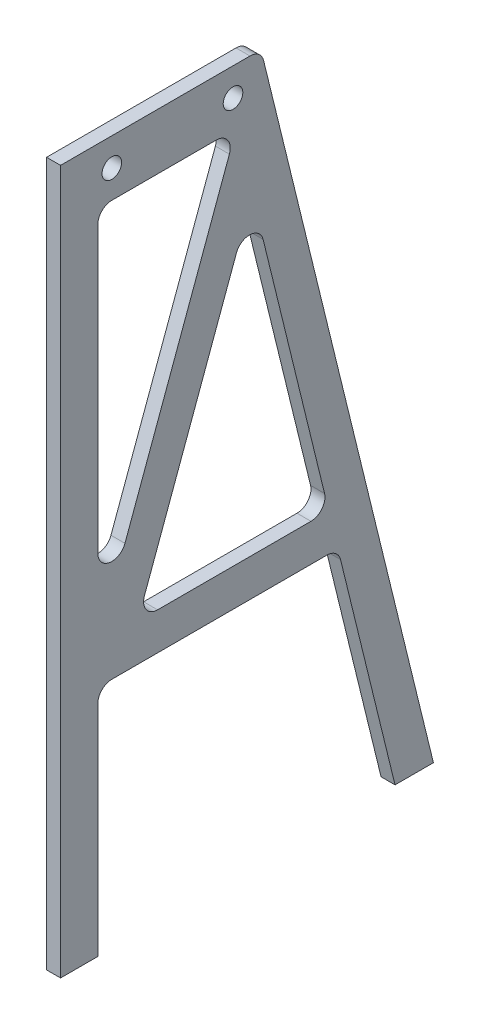
SolidWorks part; units mm, degrees
material "Thornel Mat VMA"
ref_plane "Front Plane" through (0, 0, 0) normal (0, 0, 1) x (1, 0, 0)
ref_plane "Top Plane" through (0, 0, 0) normal (0, 1, 0) x (1, 0, 0)
ref_plane "Right Plane" through (0, 0, 0) normal (1, 0, 0) x (0, 0, -1)
sketch "Sketch1" plane through (0, 0, 0) normal (1, 0, 0) x (0, 0, -1)
  line L0 (0, 0) -> (0, 75.5)
  line L2 (21.5, 75.5) -> (40, 0)
  line L3 (40, 0) -> (35.8817, 0)
  line L4 (35.8817, 0) -> (29.7558, 25)
  line L5 (29.7558, 25) -> (4, 25)
  line L6 (4, 25) -> (4, 0)
  line L7 (4, 0) -> (0, 0)
  line L8 (4, 69.5) -> (18.8519, 69.5)
  line L9 (18.8519, 69.5) -> (4, 29)
  line L10 (4, 29) -> (4, 69.5)
  line L11 (8.2605, 29) -> (20.5584, 62.5355)
  line L12 (20.5584, 62.5355) -> (28.7757, 29)
  line L13 (28.7757, 29) -> (8.2605, 29)
  line L15 (21.5, 75.5) -> (0, 75.5)
  circle A0 centre (5.5, 72.5) radius 1.05
  circle A1 centre (18.5, 72.5) radius 1.05
  point P18 (21.5, 75.6947)
  point P20 (0, 75.7334)
  dimension "D4" = 2.1
  dimension "D1" = 4
  dimension "D2" = 4
  dimension "D3" = 25
  dimension "D5" = 72.5
  dimension "D6" = 40
  dimension "D8" = 13
  dimension "D9" = 5.5
  dimension "D10" = 3
  dimension "D11" = 4
  dimension "D12" = 3
  dimension "D13" = 4
  dimension "D7" = 3
extrude "Boss-Extrude1" add sketch "Sketch1" along normal blind 1.5
fillet "Fillet1" radius 1.5 9 edges at (0.75, 29, -4) (0.75, 29, -8.2605) (0.75, 25, -29.7558) (0.75, 25, -4) (0.75, 69.5, -4) (0.75, 69.5, -18.8519) (0.75, 62.5355, -20.5584) (0.75, 29, -28.7757) (0.75, 75.5, -21.5)
equation "\"D2@Sketch1\"=\"D1@Sketch1\""
equation "\"D10@Sketch1\"=\"D7@Sketch1\""
equation "\"D11@Sketch1\"=\"D1@Sketch1\""
equation "\"D12@Sketch1\"=\"D7@Sketch1\""
equation "\"D13@Sketch1\"=\"D1@Sketch1\""
